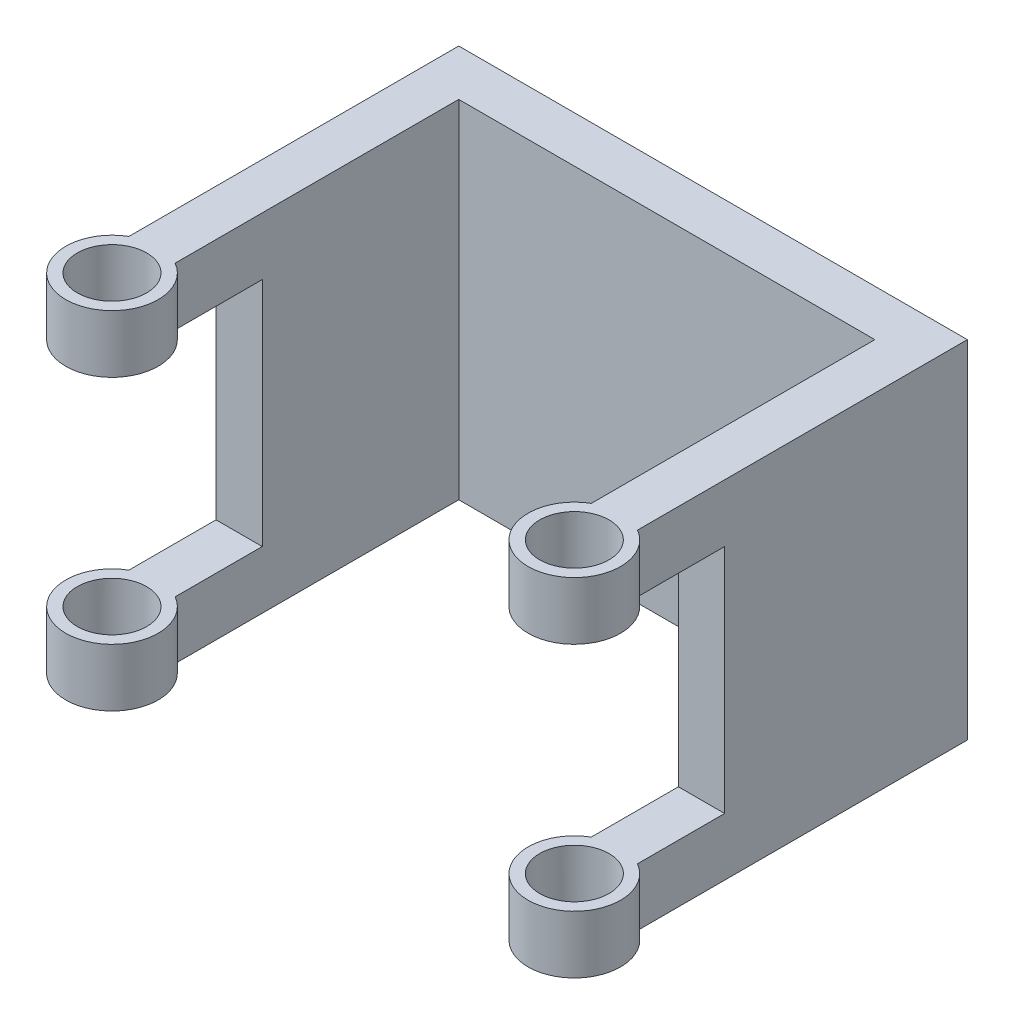
SolidWorks part; units mm, degrees
ref_plane "Front Plane" through (0, 0, 0) normal (0, 0, 1) x (1, 0, 0)
ref_plane "Top Plane" through (0, 0, 0) normal (0, 1, 0) x (1, 0, 0)
ref_plane "Right Plane" through (0, 0, 0) normal (1, 0, 0) x (0, 0, -1)
sketch "Sketch1" plane through (0, 0, 0) normal (0, 1, 0) x (1, 0, 0)
  line L0 (0, 0) -> (0, 15) construction
  line L1 (0, 15) -> (20, 15) construction
  line L2 (20, 15) -> (20, 0) construction
  line L3 (1, 1.7321) -> (1, 14)
  line L4 (1, 14) -> (19, 14)
  line L5 (19, 14) -> (19, 1.7321)
  line L6 (-1, 1.7321) -> (-1, 16)
  line L7 (-1, 16) -> (21, 16)
  line L8 (21, 16) -> (21, 1.7321)
  line L10 (1, 0) -> (1, 14) construction
  line L11 (-1, 0) -> (-1, 16) construction
  line L12 (19, 14) -> (19, 0) construction
  line L13 (21, 16) -> (21, 0) construction
  arc A0 (-1, 1.7321) -> (1, 1.7321) centre (0, 0) ccw
  arc A1 (19, 1.7321) -> (21, 1.7321) centre (20, 0) ccw
  dimension "D1" = 4
  dimension "D3" = 4
  dimension "D2" = 20
  dimension "D4" = 1
  dimension "D6" = 15
  dimension "D5" = 2
extrude "Boss-Extrude1" add sketch "Sketch1" along normal blind 15
sketch "Sketch2" plane through (0, 0, 0) normal (1, 0, 0) x (0, 0, -1)
  line L0 (1.7321, 15) -> (1.7321, 0) construction
  line L1 (5.5, 12.5) -> (-2, 12.5)
  line L2 (5.5, 12.5) -> (5.5, 2.5)
  line L3 (5.5, 2.5) -> (-2, 2.5)
  line L4 (-2, 12.5) -> (-2, 2.5)
  line L5 (16, 15) -> (1.7321, 15) construction
  line L6 (-2, 15) -> (-2, 0) construction
  point P4 (5.5, 7.5)
  point P7 (1.7321, 7.5)
  dimension "D1" = 2.5
  dimension "D2" = 7.5
extrude "Cut-Extrude1" cut sketch "Sketch2" against normal through all both and the other way through all
sketch "Sketch3" plane through (0, 15, 0) normal (0, 1, 0) x (1, 0, 0)
  circle A0 centre (0, 0) radius 1.5
  circle A1 centre (20, 0) radius 1.5
extrude "Cut-Extrude2" cut sketch "Sketch3" against normal through all
